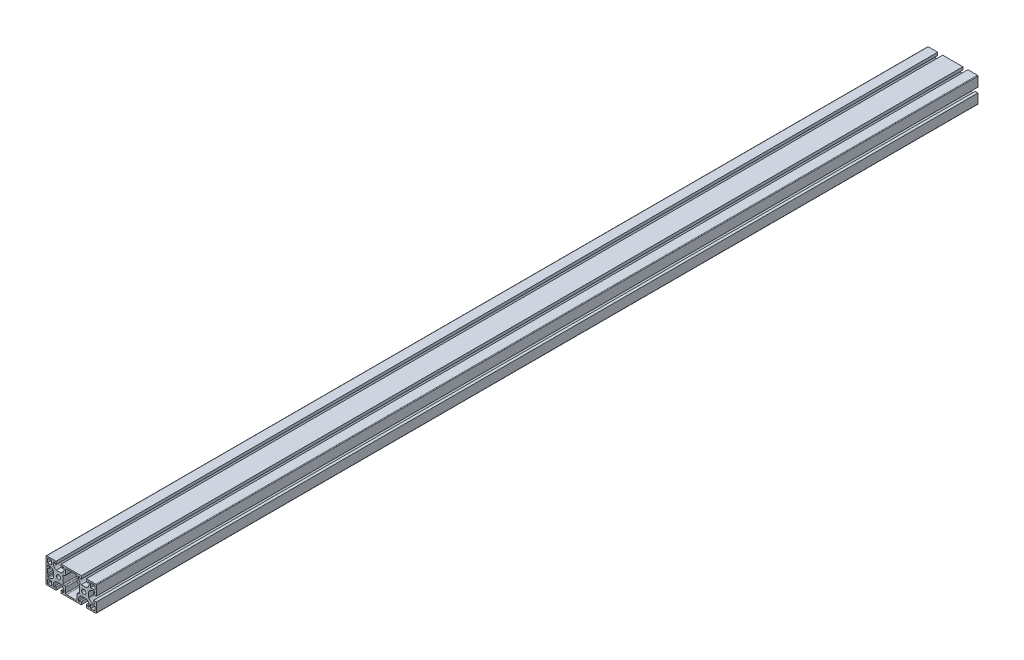
SolidWorks part; units mm, degrees
material "3.0255 (EN-AW 1350A)"
ref_plane "Płaszczyzna przednia" through (0, 0, 0) normal (0, 0, 1) x (1, 0, 0)
ref_plane "Płaszczyzna górna" through (0, 0, 0) normal (0, 1, 0) x (1, 0, 0)
ref_plane "Płaszczyzna prawa" through (0, 0, 0) normal (1, 0, 0) x (0, 0, -1)
sketch "Szkic1" plane through (0, 0, 0) normal (0, 0, 1) x (1, 0, 0)
  line L0 (0, 20) -> (0, -20) construction
  line L1 (-51.8865, 0) -> (40, 0) construction
  line L4 (-40, -19) -> (-40, 19)
  line L7 (-40, -20) -> (0, 0) construction
  line L8 (-40, 20) -> (40, -20) construction
  line L13 (20, 20) -> (20, 0) construction
  line L15 (24, 20) -> (24, 15.5)
  line L16 (24, 15.5) -> (26.4714, 15.5)
  line L21 (16, 15.5) -> (13.5286, 15.5)
  line L23 (16, 20) -> (13.5286, 20)
  line L24 (16, 20) -> (16, 15.5)
  line L25 (16, 7.75) -> (24, 7.75)
  line L26 (13.5286, 15.5) -> (13.5286, 17.75)
  line L27 (26.4714, 15.5) -> (26.4714, 17.75)
  line L28 (-24, 20) -> (-24, 15.5)
  line L29 (-26.4714, 15.5) -> (-26.4714, 17.75)
  line L30 (-24, 15.5) -> (-26.4714, 15.5)
  line L31 (-13.5286, 15.5) -> (-13.5286, 17.75)
  line L32 (-16, 15.5) -> (-13.5286, 15.5)
  line L33 (-16, 20) -> (-16, 15.5)
  line L34 (-16, 7.75) -> (-24, 7.75)
  line L35 (20, -20) -> (20, 0) construction
  line L36 (-40, -20) -> (0, 0) construction
  line L37 (-40, 20) -> (40, -20) construction
  line L38 (30.9714, -17.75) -> (36.75, -17.75)
  line L39 (-16, -7.75) -> (-24, -7.75)
  line L40 (-16, -20) -> (-16, -15.5)
  line L41 (-16, -15.5) -> (-13.5286, -15.5)
  line L42 (-13.5286, -15.5) -> (-13.5286, -17.75)
  line L43 (-24, -15.5) -> (-26.4714, -15.5)
  line L44 (-26.4714, -15.5) -> (-26.4714, -17.75)
  line L45 (-24, -20) -> (-24, -15.5)
  line L46 (26.4714, -15.5) -> (26.4714, -17.75)
  line L47 (13.5286, -15.5) -> (13.5286, -17.75)
  line L48 (16, -7.75) -> (24, -7.75)
  line L49 (16, -20) -> (16, -15.5)
  line L50 (16, -15.5) -> (13.5286, -15.5)
  line L51 (24, -15.5) -> (26.4714, -15.5)
  line L52 (24, -20) -> (24, -15.5)
  line L53 (40, -20) -> (0, 20) construction
  line L54 (35.5, 6.4714) -> (37.75, 6.4714)
  line L55 (35.5, 4) -> (35.5, 6.4714)
  line L56 (40, 4) -> (35.5, 4)
  line L57 (40, -4) -> (35.5, -4)
  line L58 (35.5, -4) -> (35.5, -6.4714)
  line L59 (35.5, -6.4714) -> (37.75, -6.4714)
  line L60 (27.75, 4) -> (27.75, -4)
  line L61 (-35.5, -6.4714) -> (-37.75, -6.4714)
  line L62 (-37.75, -4) -> (-35.5, -4)
  line L63 (-35.5, -4) -> (-35.5, -6.4714)
  line L64 (-35.5, 4) -> (-35.5, 6.4714)
  line L65 (-35.5, 6.4714) -> (-37.75, 6.4714)
  line L66 (-37.75, 4) -> (-35.5, 4)
  line L67 (-27.75, 4) -> (-27.75, -4)
  line L68 (-37.75, 4) -> (-37.75, -4)
  line L69 (40, -4) -> (40, -19)
  line L70 (40, 19) -> (40, 4)
  line L71 (-39, -20) -> (-24, -20)
  line L72 (-16, -20) -> (16, -20)
  line L73 (24, -20) -> (39, -20)
  line L74 (13.5286, 20) -> (-16, 20)
  line L75 (-24, 20) -> (-39, 20)
  line L76 (24, 20) -> (39, 20)
  line L77 (10.5286, 7.0902) -> (11.4095, 7.0902)
  line L78 (-7.5286, -17.75) -> (7.5286, -17.75)
  line L79 (-9.0286, -16.25) -> (-9.0286, -8.5902)
  line L80 (-7.5286, 17.75) -> (7.5286, 17.75)
  line L81 (9.0286, -16.25) -> (9.0286, -8.5902)
  line L82 (-9.0286, -17.75) -> (9.0286, 17.75) construction
  line L83 (-9.0286, 17.75) -> (9.0286, -17.75) construction
  line L84 (-11.4095, -7.0902) -> (-10.5286, -7.0902)
  line L85 (-12.9095, -5.5902) -> (-12.9095, 5.5902)
  line L86 (-11.4095, 7.0902) -> (-10.5286, 7.0902)
  line L87 (12.9095, -5.5902) -> (12.9095, 5.5902)
  line L88 (-12.9095, -7.0902) -> (0, 0) construction
  line L89 (-12.9095, 7.0902) -> (12.9095, -7.0902) construction
  line L90 (-9.0286, 8.5902) -> (-9.0286, 16.25)
  line L91 (-9.0286, 4.5143) -> (-9.0286, 4.9587)
  line L92 (-9.0286, -4.9587) -> (-9.0286, -4.5143)
  line L93 (9.0286, 8.5902) -> (9.0286, 16.25)
  line L94 (10.5286, -7.0902) -> (11.4095, -7.0902)
  line L96 (0, 0) -> (12.9095, 7.0902) construction
  line L98 (37.75, -10.9714) -> (37.75, -16.75)
  line L99 (30.9714, 10.9714) -> (37.75, 10.9714)
  line L100 (30.9714, 10.9714) -> (30.9714, 17.75)
  line L101 (30.9714, 17.75) -> (36.75, 17.75)
  line L102 (37.75, 10.9714) -> (37.75, 16.75)
  line L103 (30.9714, 10.9714) -> (37.75, 17.75) construction
  line L104 (30.9714, 17.75) -> (37.75, 10.9714) construction
  line L105 (30.9714, -10.9714) -> (37.75, -10.9714)
  line L106 (30.9714, -10.9714) -> (30.9714, -17.75)
  line L107 (-30.9714, -10.9714) -> (-30.9714, -17.75)
  line L108 (-30.9714, -10.9714) -> (-37.75, -10.9714)
  line L109 (-37.75, -10.9714) -> (-37.75, -16.75)
  line L110 (-30.9714, -17.75) -> (-36.75, -17.75)
  line L111 (-30.9714, 17.75) -> (-36.75, 17.75)
  line L112 (-37.75, 10.9714) -> (-37.75, 16.75)
  line L113 (-30.9714, 10.9714) -> (-37.75, 10.9714)
  line L114 (-30.9714, 10.9714) -> (-30.9714, 17.75)
  circle A0 centre (-20, 0) radius 3.4
  circle A1 centre (20, 0) radius 3.4
  arc A2 (26.4714, 17.75) -> (28.7214, 15.5) centre (26.4714, 15.5) cw
  arc A3 (28.7214, 15.5) -> (24, 7.75) centre (20, 15.5) cw
  arc A4 (13.5286, 17.75) -> (11.2786, 15.5) centre (13.5286, 15.5) ccw
  arc A5 (11.2786, 15.5) -> (16, 7.75) centre (20, 15.5) ccw
  arc A6 (-26.4714, 17.75) -> (-28.7214, 15.5) centre (-26.4714, 15.5) ccw
  arc A7 (-13.5286, 17.75) -> (-11.2786, 15.5) centre (-13.5286, 15.5) cw
  arc A8 (-11.2786, 15.5) -> (-16, 7.75) centre (-20, 15.5) cw
  arc A9 (-28.7214, 15.5) -> (-24, 7.75) centre (-20, 15.5) ccw
  arc A10 (-28.7214, -15.5) -> (-24, -7.75) centre (-20, -15.5) cw
  arc A11 (-11.2786, -15.5) -> (-16, -7.75) centre (-20, -15.5) ccw
  arc A12 (-13.5286, -17.75) -> (-11.2786, -15.5) centre (-13.5286, -15.5) ccw
  arc A13 (-26.4714, -17.75) -> (-28.7214, -15.5) centre (-26.4714, -15.5) cw
  arc A14 (11.2786, -15.5) -> (16, -7.75) centre (20, -15.5) cw
  arc A15 (13.5286, -17.75) -> (11.2786, -15.5) centre (13.5286, -15.5) cw
  arc A16 (28.7214, -15.5) -> (24, -7.75) centre (20, -15.5) ccw
  arc A17 (26.4714, -17.75) -> (28.7214, -15.5) centre (26.4714, -15.5) ccw
  arc A18 (35.5, 8.7214) -> (27.75, 4) centre (35.5, 0) ccw
  arc A19 (37.75, 6.4714) -> (35.5, 8.7214) centre (35.5, 6.4714) ccw
  arc A20 (37.75, -6.4714) -> (35.5, -8.7214) centre (35.5, -6.4714) cw
  arc A21 (35.5, -8.7214) -> (27.75, -4) centre (35.5, 0) cw
  arc A22 (-35.5, -8.7214) -> (-27.75, -4) centre (-35.5, 0) ccw
  arc A23 (-37.75, -6.4714) -> (-35.5, -8.7214) centre (-35.5, -6.4714) ccw
  arc A24 (-37.75, 6.4714) -> (-35.5, 8.7214) centre (-35.5, 6.4714) cw
  arc A25 (-35.5, 8.7214) -> (-27.75, 4) centre (-35.5, 0) cw
  arc A26 (-10.5286, 7.0902) -> (-9.0286, 8.5902) centre (-10.5286, 8.5902) ccw
  arc A27 (-9.0286, -8.5902) -> (-10.5286, -7.0902) centre (-10.5286, -8.5902) ccw
  arc A28 (11.4095, -7.0902) -> (12.9095, -5.5902) centre (11.4095, -5.5902) ccw
  arc A29 (9.0286, -8.5902) -> (10.5286, -7.0902) centre (10.5286, -8.5902) cw
  arc A30 (7.5286, -17.75) -> (9.0286, -16.25) centre (7.5286, -16.25) ccw
  arc A31 (-7.5286, -17.75) -> (-9.0286, -16.25) centre (-7.5286, -16.25) cw
  arc A32 (-11.4095, -7.0902) -> (-12.9095, -5.5902) centre (-11.4095, -5.5902) cw
  arc A33 (-12.9095, 5.5902) -> (-11.4095, 7.0902) centre (-11.4095, 5.5902) cw
  arc A34 (-9.0286, 16.25) -> (-7.5286, 17.75) centre (-7.5286, 16.25) cw
  arc A35 (7.5286, 17.75) -> (9.0286, 16.25) centre (7.5286, 16.25) cw
  arc A36 (11.4095, 7.0902) -> (12.9095, 5.5902) centre (11.4095, 5.5902) cw
  arc A37 (10.5286, 7.0902) -> (9.0286, 8.5902) centre (10.5286, 8.5902) cw
  arc A38 (-40, 19) -> (-39, 20) centre (-39, 19) cw
  arc A39 (-39, -20) -> (-40, -19) centre (-39, -19) cw
  arc A40 (39, -20) -> (40, -19) centre (39, -19) ccw
  arc A41 (39, 20) -> (40, 19) centre (39, 19) cw
  arc A42 (36.75, 17.75) -> (37.75, 16.75) centre (36.75, 16.75) cw
  arc A43 (36.75, -17.75) -> (37.75, -16.75) centre (36.75, -16.75) ccw
  arc A44 (-36.75, -17.75) -> (-37.75, -16.75) centre (-36.75, -16.75) cw
  arc A45 (-36.75, 17.75) -> (-37.75, 16.75) centre (-36.75, 16.75) ccw
  point P5 (0, 0)
  point P17 (0, 0)
  point P30 (24, 17.75)
  point P108 (0, 0)
  point P124 (-9.0286, 7.0902)
  point P132 (9.0286, -7.0902)
  point P156 (9.0286, 7.0902)
  point P161 (40, 20)
  point P162 (34.3607, 14.3607)
  point P168 (37.75, 17.75)
  point P169 (30.2944, 10.2944)
  point P170 (30.124, 10.124)
  point P171 (0, 0)
  point P172 (0, 0)
  point P173 (37.6841, 17.6841)
  dimension "D4" = 6.8
  dimension "D5" = 12.25
  dimension "D9" = 11
  dimension "D11" = 1.5
  dimension "D12" = 1
  dimension "D16" = 1
  dimension "D1" = 80
  dimension "D2" = 40
  dimension "D3" = 40
  dimension "D6" = 2.25
  dimension "D7" = 8
  dimension "D8" = 4.5
  dimension "D10" = 14.1804
  dimension "D13" = 2.25
  dimension "D14" = 2.25
  dimension "D15" = 2.25
extrude "Dodanie-wyciągnięcie1" add sketch "Szkic1" along normal blind 1400 contours A20 A21 L60 A18 A19 L54 L55 L56 L70 L76 L15 L16 L27 A2 A3 L25 A5 A4 L26 L21 L24 L23 L74 L33 L32 L31 A7 A8 L34 A9 A6 L29 L30 L28 L75 L4 L71 L45 L43 L44 A13 A10 L39 A11 A12 L42 L41 L40 L72 L49 L50
